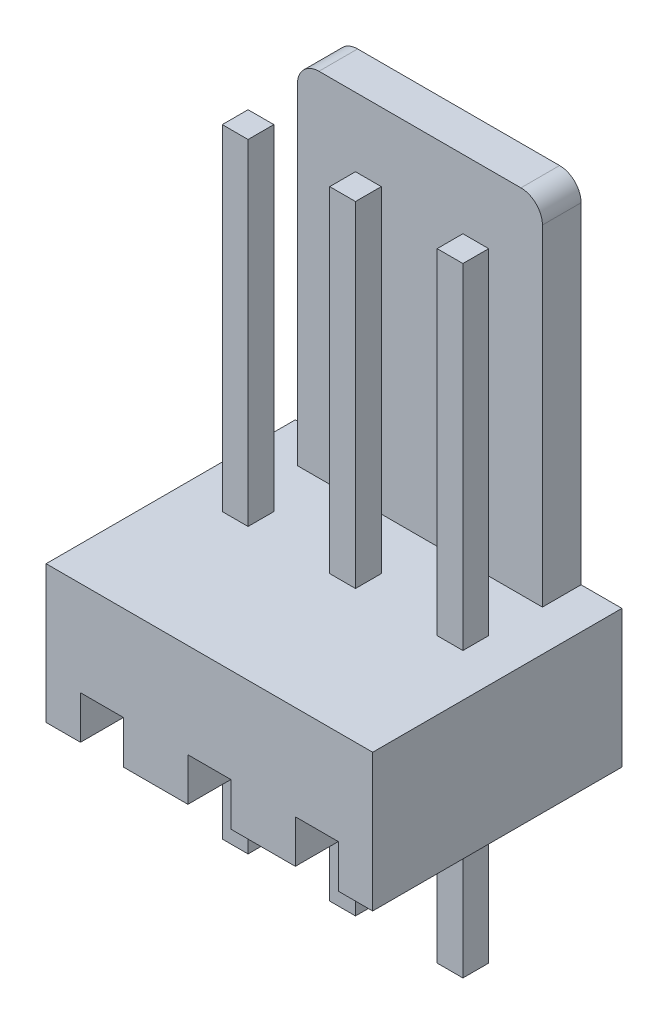
SolidWorks part; units mm, degrees
ref_plane "Alzado" through (0, 0, 0) normal (0, 0, 1) x (1, 0, 0)
ref_plane "Planta" through (0, 0, 0) normal (0, 1, 0) x (1, 0, 0)
ref_plane "Vista lateral" through (0, 0, 0) normal (1, 0, 0) x (0, 0, -1)
sketch "Croquis1" plane through (0, 0, 0) normal (0, 1, 0) x (1, 0, 0)
  line L1 (-3.8, 2.9) -> (3.8, 2.9)
  line L2 (-3.8, 2.9) -> (-3.8, -2.9)
  line L3 (-3.8, -2.9) -> (3.8, -2.9)
  line L4 (3.8, 2.9) -> (3.8, -2.9)
  line L5 (-3.8, 2.9) -> (3.8, -2.9) construction
  line L6 (-3.8, -2.9) -> (3.8, 2.9) construction
  point P0 (0, 0)
  dimension "D1" = 5.8
  dimension "D2" = 7.6
extrude "Saliente-Extruir1" add sketch "Croquis1" along normal blind 3.2
sketch "Croquis2" plane through (0, 3.2, 0) normal (0, 1, 0) x (1, 0, 0)
  line L0 (-3.8, 2.9) -> (-2.85, 2.9) construction
  line L1 (3.8, 2.9) -> (-3.8, 2.9) construction
  line L2 (-2.85, 2.9) -> (2.85, 2.9) construction
  line L3 (2.85, 2.9) -> (3.8, 2.9) construction
  line L4 (-2.85, 2.9) -> (2.85, 2.9)
  line L5 (-2.85, 2.9) -> (-2.85, 2)
  line L6 (2.85, 2.9) -> (2.85, 2)
  line L7 (-2.85, 2) -> (2.85, 2)
  dimension "D1" = 0.95
  dimension "D2" = 5.7
  dimension "D3" = 0.95
  dimension "D4" = 0.9
extrude "Saliente-Extruir2" add sketch "Croquis2" along normal blind 8.2
fillet "Redondeo2" radius 0.5 2 edges at (2.85, 11.4, -2.45)
fillet "Redondeo3" radius 0.5 2 edges at (-2.85, 11.4, -2.45)
sketch "Croquis3" plane through (0, 0, 0) normal (0, -1, 0) x (1, 0, 0)
  line L0 (-3.8, 2.9) -> (-3, 2.9) construction
  line L1 (-3.8, 2.9) -> (3.8, 2.9) construction
  line L2 (-3, 2.9) -> (-2, 2.9) construction
  line L3 (-2, 2.9) -> (-0.5, 2.9) construction
  line L4 (-0.5, 2.9) -> (0.5, 2.9) construction
  line L5 (0.5, 2.9) -> (2, 2.9) construction
  line L6 (2, 2.9) -> (3, 2.9) construction
  line L7 (3, 2.9) -> (3.8, 2.9) construction
  line L8 (-3, 2.9) -> (-2, 2.9)
  line L9 (-2, 2.9) -> (-2, -2.9)
  line L10 (3.8, -2.9) -> (-3.8, -2.9) construction
  line L11 (-2, -2.9) -> (-3, -2.9)
  line L12 (-3, -2.9) -> (-3, 2.9)
  line L13 (-0.5, 2.9) -> (-0.5, -2.9)
  line L14 (-0.5, -2.9) -> (0.5, -2.9)
  line L15 (0.5, -2.9) -> (0.5, 2.9)
  line L16 (0.5, 2.9) -> (-0.5, 2.9)
  line L17 (2, 2.9) -> (3, 2.9)
  line L18 (3, 2.9) -> (3, -2.9)
  line L19 (3, -2.9) -> (2, -2.9)
  line L20 (2, -2.9) -> (2, 2.9)
  dimension "D1" = 0.8
  dimension "D2" = 1
  dimension "D3" = 1.5
  dimension "D4" = 1
  dimension "D5" = 1.5
  dimension "D6" = 1
  dimension "D7" = 0.8
extrude "Cortar-Extruir1" cut sketch "Croquis3" against normal blind 1
sketch "Croquis4" plane through (0, 1, 0) normal (0, -1, 0) x (1, 0, 0)
  line L0 (-2, 2.9) -> (-2, -0.8) construction
  line L1 (-2, -2.9) -> (-2, 2.9) construction
  line L2 (-2, -0.8) -> (-3, -0.8) construction
  line L3 (-3, 2.9) -> (-3, -2.9) construction
  line L4 (-3, -0.8) -> (-2.8, -0.8) construction
  line L5 (-2.8, -0.8) -> (-2.2, -0.8) construction
  line L6 (-2.2, -0.8) -> (-2, -0.8) construction
  line L7 (-2.2, -0.8) -> (-2.8, -0.8)
  line L8 (-2.2, -0.8) -> (-2.2, -0.2)
  line L9 (-2.8, -0.8) -> (-2.8, -0.2)
  line L10 (-2.2, -0.2) -> (-2.8, -0.2)
  line L11 (-0.5, 2.9) -> (-0.5, -0.8) construction
  line L12 (-0.5, 2.9) -> (-0.5, -2.9) construction
  line L13 (-0.5, -0.8) -> (-0.3, -0.8) construction
  line L14 (-0.3, -0.8) -> (0.3, -0.8) construction
  line L15 (0.3, -0.8) -> (0.5, -0.8) construction
  line L16 (0.5, -2.9) -> (0.5, 2.9) construction
  line L17 (0.3, -0.8) -> (-0.3, -0.8)
  line L18 (0.3, -0.8) -> (0.3, -0.2)
  line L19 (-0.3, -0.8) -> (-0.3, -0.2)
  line L20 (0.3, -0.2) -> (-0.3, -0.2)
  line L21 (2, 2.9) -> (2, -0.8) construction
  line L22 (2, 2.9) -> (2, -2.9) construction
  line L23 (2, -0.8) -> (2.2, -0.8) construction
  line L24 (2.2, -0.8) -> (2.8, -0.8) construction
  line L25 (2.8, -0.8) -> (3, -0.8) construction
  line L26 (3, -2.9) -> (3, 2.9) construction
  line L27 (2.8, -0.8) -> (2.2, -0.8)
  line L28 (2.8, -0.8) -> (2.8, -0.2)
  line L29 (2.2, -0.8) -> (2.2, -0.2)
  line L30 (2.8, -0.2) -> (2.2, -0.2)
  dimension "D6" = 0.2
  dimension "D1" = 0.2
  dimension "D2" = 0.6
  dimension "D3" = 0.2
  dimension "D4" = 3.7
  dimension "D5" = 0.6
  dimension "D7" = 0.6
  dimension "D8" = 0.2
  dimension "D9" = 0.6
  dimension "D10" = 0.2
  dimension "D11" = 0.6
  dimension "D12" = 0.2
  dimension "D13" = 0.6
extrude "Saliente-Extruir3" add sketch "Croquis4" along normal blind 4.4 and the other way blind 10
